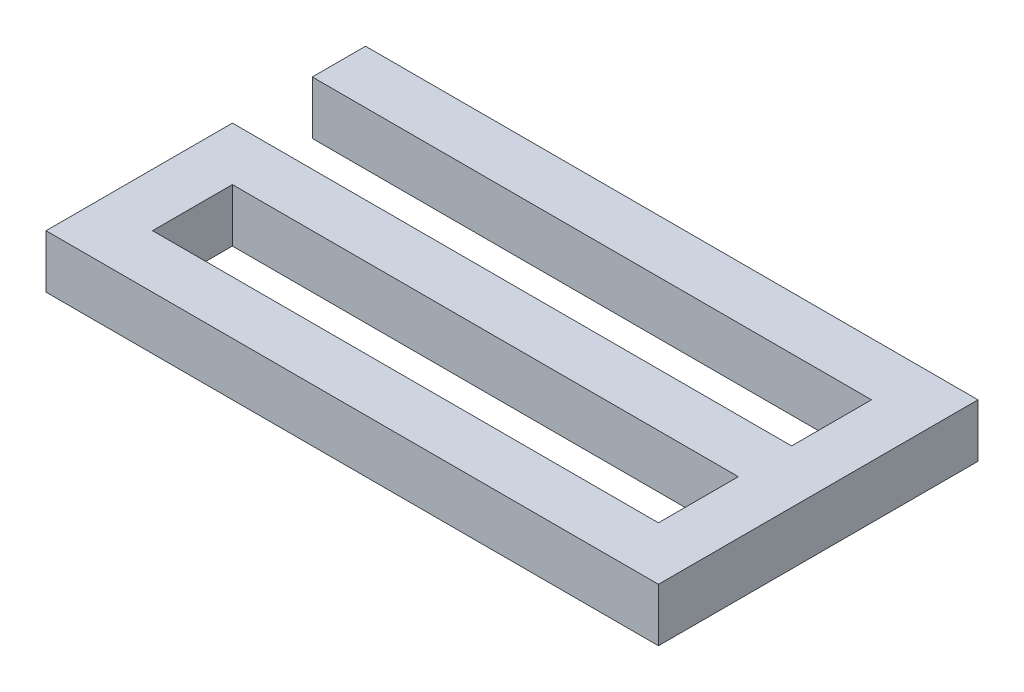
SolidWorks part; units mm, degrees
ref_plane "Plano frontal" through (0, 0, 0) normal (0, 0, 1) x (1, 0, 0)
ref_plane "Plano superior" through (0, 0, 0) normal (0, 1, 0) x (1, 0, 0)
ref_plane "Plano direito" through (0, 0, 0) normal (1, 0, 0) x (0, 0, -1)
sketch "Esboço1" plane through (0, 0, 0) normal (0, 1, 0) x (1, 0, 0)
  line L1 (-10.4795, 11.375) -> (12.5205, 11.375)
  line L2 (-10.4795, 11.375) -> (-10.4795, 9.375)
  line L3 (-10.4795, 9.375) -> (10.5205, 9.375)
  line L6 (12.5205, 11.375) -> (12.5205, -0.625)
  line L7 (12.5205, -0.625) -> (10.5205, -0.625)
  line L8 (10.5205, 9.375) -> (10.5205, 6.375)
  line L9 (10.5205, -0.625) -> (-10.4795, -0.625)
  line L11 (10.5205, 1.375) -> (-8.4795, 1.375)
  line L13 (-10.4795, 6.375) -> (10.5205, 6.375)
  line L14 (-10.4795, 6.375) -> (-10.4795, -0.625)
  line L15 (-8.4795, 4.375) -> (10.5205, 4.375)
  line L17 (-8.4795, 4.375) -> (-8.4795, 1.375)
  line L18 (10.5205, 4.375) -> (10.5205, 1.375)
  dimension "D1" = 2
  dimension "D2" = 23
  dimension "D9" = 19
extrude "Ressalto-extrusão1" add sketch "Esboço1" along normal blind 2
